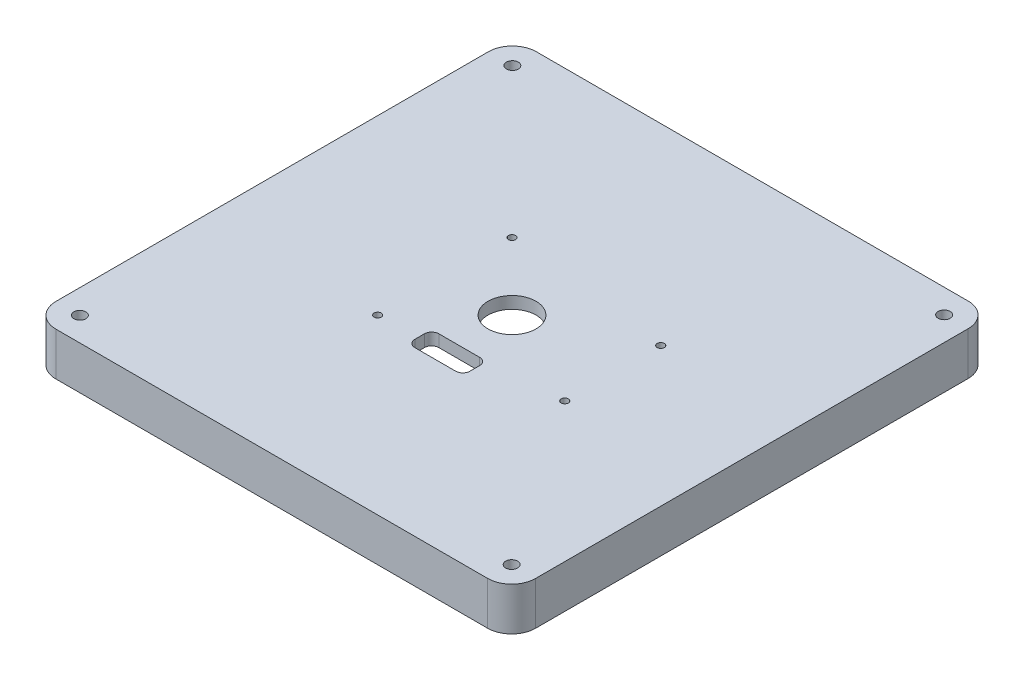
SolidWorks part; units mm, degrees
ref_plane "前视基准面" through (0, 0, 0) normal (0, 0, 1) x (1, 0, 0)
ref_plane "上视基准面" through (0, 0, 0) normal (0, 1, 0) x (1, 0, 0)
ref_plane "右视基准面" through (0, 0, 0) normal (1, 0, 0) x (0, 0, -1)
sketch "Sketch1" plane through (0, 0, 0) normal (0, 1, 0) x (1, 0, 0)
  line L1 (-100, 100.15) -> (100, 100.15)
  line L2 (-100, 100.15) -> (-100, -100.15)
  line L3 (-100, -100.15) -> (100, -100.15)
  line L4 (100, 100.15) -> (100, -100.15)
  line L5 (-100, 100.15) -> (100, -100.15) construction
  line L6 (-100, -100.15) -> (100, 100.15) construction
  point P0 (0, 0)
  dimension "D1" = 200.3
  dimension "D2" = 200
extrude "Boss-Extrude1" add sketch "Sketch1" along normal blind 18
fillet "Fillet1" radius 10 4 edges at (-100, 9, -100.15) (-100, 9, 100.15) (100, 9, -100.15) (100, 9, 100.15)
sketch "Sketch2" plane through (0, 0, 0) normal (0, -1, 0) x (1, 0, 0)
  line L1 (-75, 50) -> (75, 50)
  line L2 (-75, 50) -> (-75, -50)
  line L3 (-75, -50) -> (75, -50)
  line L4 (75, 50) -> (75, -50)
  line L5 (-75, 50) -> (75, -50) construction
  line L6 (-75, -50) -> (75, 50) construction
  point P0 (0, 0)
  dimension "D1" = 150
  dimension "D2" = 100
extrude "Cut-Extrude1" cut sketch "Sketch2" against normal blind 13
fillet "Fillet2" radius 10 4 edges at (75, 6.5, -50) (-75, 6.5, -50) (-75, 6.5, 50) (75, 6.5, 50)
sketch "Sketch3" plane through (0, 0, 0) normal (0, -1, 0) x (1, 0, 0)
  circle A0 centre (-90, 90.15) radius 5
  circle A1 centre (90, 90.15) radius 5
  circle A2 centre (90, -90.15) radius 5
  circle A3 centre (-90, -90.15) radius 5
extrude "Cut-Extrude2" cut sketch "Sketch3" against normal blind 5
sketch "Sketch4" plane through (0, 5, 0) normal (0, -1, 0) x (1, 0, 0)
  circle A0 centre (-90, 90.15) radius 2.5
  circle A1 centre (90, 90.15) radius 2.5
  circle A2 centre (90, -90.15) radius 2.5
  circle A3 centre (-90, -90.15) radius 2.5
extrude "Cut-Extrude3" cut sketch "Sketch4" against normal through all
sketch "Sketch5" plane through (0, 13, 0) normal (0, -1, 0) x (1, 0, 0)
  circle A0 centre (0, 0) radius 10
extrude "Cut-Extrude4" cut sketch "Sketch5" against normal through all
sketch "Sketch6" plane through (0, 18, 0) normal (0, 1, 0) x (1, 0, 0)
  line L0 (0, 0) -> (27.9167, 0) construction
  line L1 (-11.5, -22) -> (11.5, -22)
  line L2 (-11.5, -22) -> (-11.5, -32)
  line L3 (-11.5, -32) -> (11.5, -32)
  line L4 (11.5, -22) -> (11.5, -32)
  line L5 (-11.5, -22) -> (11.5, -32) construction
  line L6 (-11.5, -32) -> (11.5, -22) construction
  circle A0 centre (-28, -28) radius 1.5
  circle A1 centre (42, -20) radius 1.5
  circle A2 centre (-28, 28) radius 1.5
  circle A3 centre (42, 20) radius 1.5
  point P0 (0, -27)
  dimension "D1" = 10
  dimension "D2" = 23
  dimension "D3" = 27
extrude "Cut-Extrude5" cut sketch "Sketch6" against normal through all
fillet "Fillet3" radius 3 4 edges at (11.5, 15.5, 22) (11.5, 15.5, 32) (-11.5, 15.5, 32) (-11.5, 15.5, 22)
